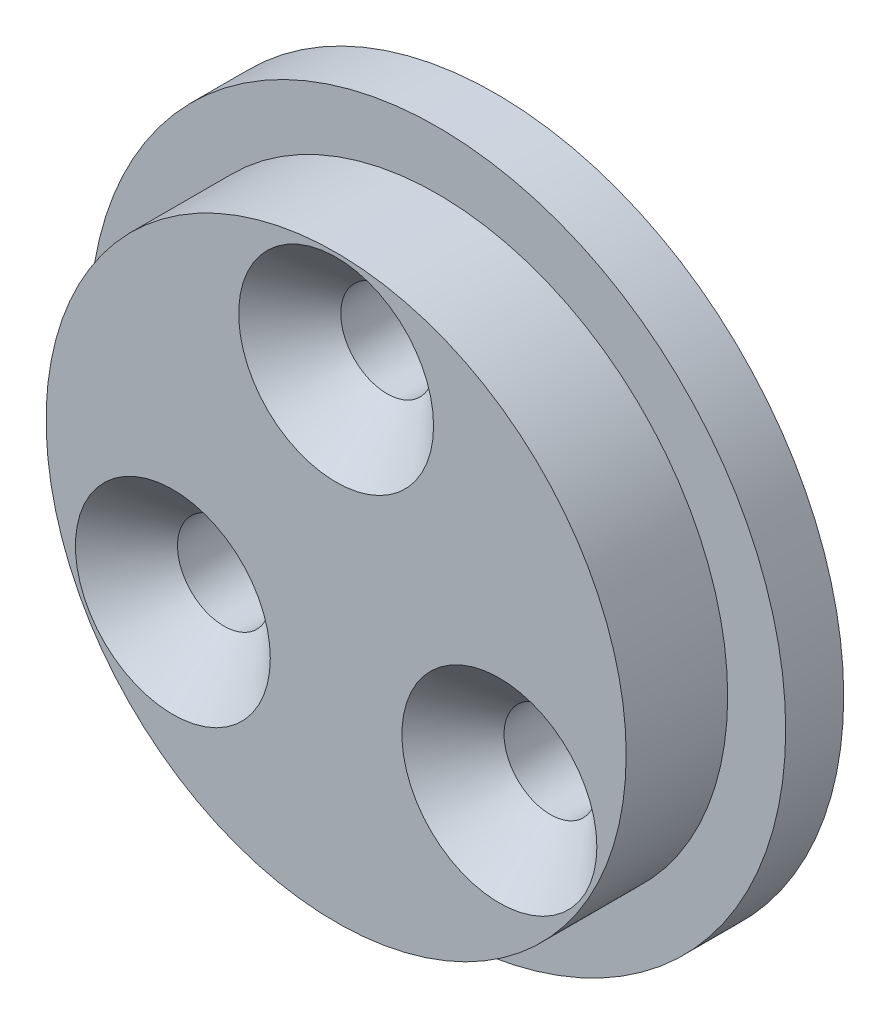
SolidWorks part; units mm, degrees
ref_plane "Front Plane" through (0, 0, 0) normal (0, 0, 1) x (1, 0, 0)
ref_plane "Top Plane" through (0, 0, 0) normal (0, 1, 0) x (1, 0, 0)
ref_plane "Right Plane" through (0, 0, 0) normal (1, 0, 0) x (0, 0, -1)
sketch "Sketch1" plane through (0, 0, 0) normal (0, 1, 0) x (1, 0, 0)
  line L0 (0, 0) -> (0, 23.9376) construction
  line L1 (0, 0) -> (3, 0)
  line L2 (3, 0) -> (3, 3)
  line L4 (10, 3) -> (10, -0.5)
  line L5 (10, -0.5) -> (0, -0.5)
  line L6 (0, -0.5) -> (0, 0)
  line L7 (10, 3) -> (12, 3)
  line L8 (12, 3) -> (12, 5)
  line L9 (9.5, 3) -> (3, 3)
  line L10 (3, 2.5) -> (0, 2.5) construction
  line L11 (9.5, 5) -> (12, 5)
  line L12 (9.5, 5) -> (9.5, 3)
  dimension "D1" = 20
  dimension "D2" = 6
  dimension "D3" = 3
  dimension "D4" = 2.5
  dimension "D5" = 0.5
  dimension "D6" = 24
  dimension "D7" = 19
  dimension "D8" = 2
revolve "Revolve1" add sketch "Sketch1" angle 360 about L0
sketch "Sketch2" plane through (0, 0, 0.5) normal (0, 0, 1) x (1, 0, 0)
sketch "Sketch4" plane through (0, 0, 0.5) normal (0, 0, 1) x (1, 0, 0)
hole_wizard "CSK for M3 SFHCS1" positions "Sketch6" profile "Sketch5" countersink size "M3" standard "ANSI Metric" end condition through all
sketch "Sketch6" plane through (0, 0, 0.5) normal (0, 0, 1) x (1, 0, 0)
  circle A0 centre (0, 0) radius 6.5 construction
  point P0 (0, 6.5)
  point P20 (5.6292, -3.25)
  point P21 (-5.6292, -3.25)
  dimension "D1" = 13
  dimension "D2" = 3
sketch "Sketch5" plane through (0, 6.5, 0.5) normal (1, 0, 0) x (0, -1, 0)
  line L0 (0, 0) -> (0, 5.5)
  line L1 (0, 5.5) -> (1.6, 5.5)
  line L2 (1.6, 5.5) -> (1.6, 1.76)
  line L3 (1.6, 1.76) -> (3.36, 0)
  line L5 (3.36, 0) -> (0, 0)
  line L6 (-1.6, 1.76) -> (-3.36, 0) construction
  line L11 (0, -6.35) -> (0, 107.95) construction
  dimension "Thru Hole Dia." = 3.2
  dimension "Thru Hole Depth" = 5.5
  dimension "Near C'Sink Dia." = 6.72
  dimension "Near C'Sink Angle" = 90
chamfer "Chamfer1" distance 0.8 angle 45 1 edges at (9.5, 0, -5)
